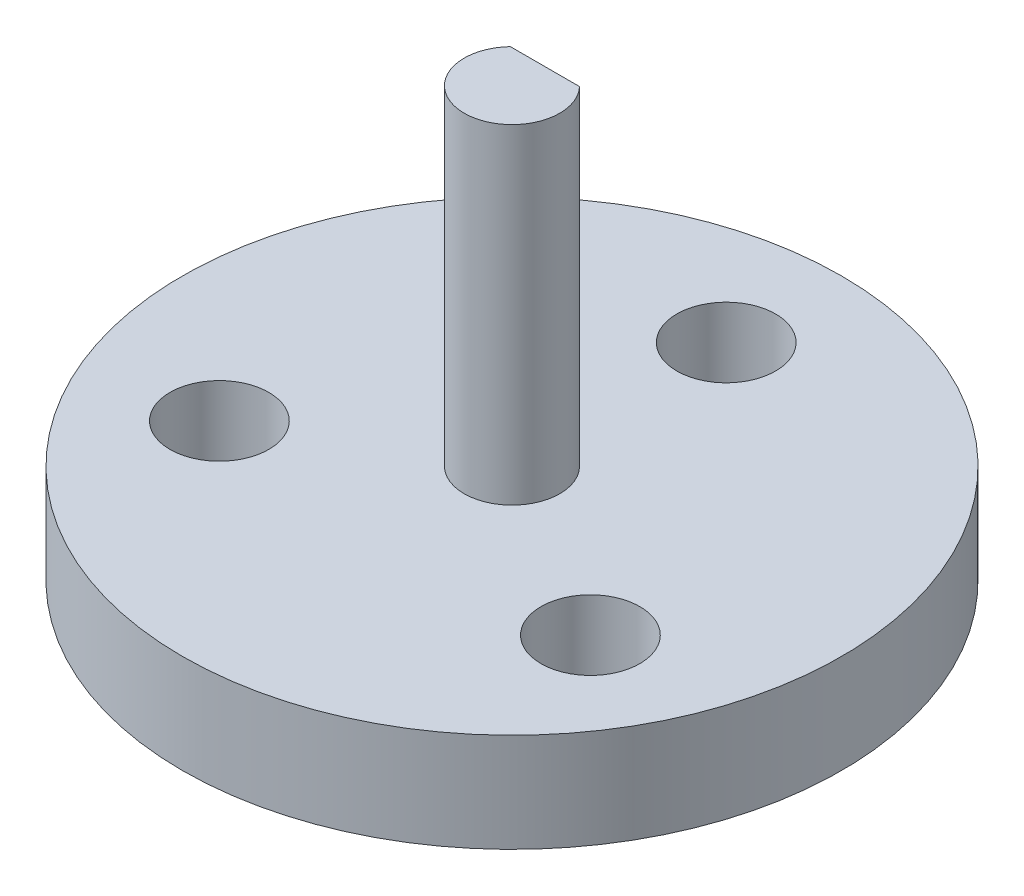
SolidWorks part; units mm, degrees
ref_plane "前视基准面" through (0, 0, 0) normal (0, 0, 1) x (1, 0, 0)
ref_plane "上视基准面" through (0, 0, 0) normal (0, 1, 0) x (1, 0, 0)
ref_plane "右视基准面" through (0, 0, 0) normal (1, 0, 0) x (0, 0, -1)
other "Configuration Table"
sketch "草图1" plane through (0, 0, 0) normal (0, 1, 0) x (1, 0, 0)
  line L0 (0, -0.2891) -> (0, -50000.2891) construction
  circle A0 centre (0, 0) radius 10
  circle A1 centre (0, 6.5) radius 1.5
  circle A4 centre (5.6292, -3.25) radius 1.5
  circle A5 centre (-5.6292, -3.25) radius 1.5
  point P14 (-0.433, 0.75)
  point P15 (0, 0)
  dimension "D1" = 20
  dimension "D2" = 6.5
  dimension "D3" = 3
extrude "凸台-拉伸1" add sketch "草图1" along normal blind 3
sketch "草图2" plane through (0, 0, 0) normal (0, 1, 0) x (1, 0, 0)
  line L3 (-1.05, 1) -> (1.05, 1)
  arc A3 (-1.05, 1) -> (1.05, 1) centre (0, 0) ccw
  point P12 (0, 0)
  dimension "D1" = 1
  dimension "D2" = 2.9
extrude "凸台-拉伸2" add sketch "草图2" along normal blind 13
